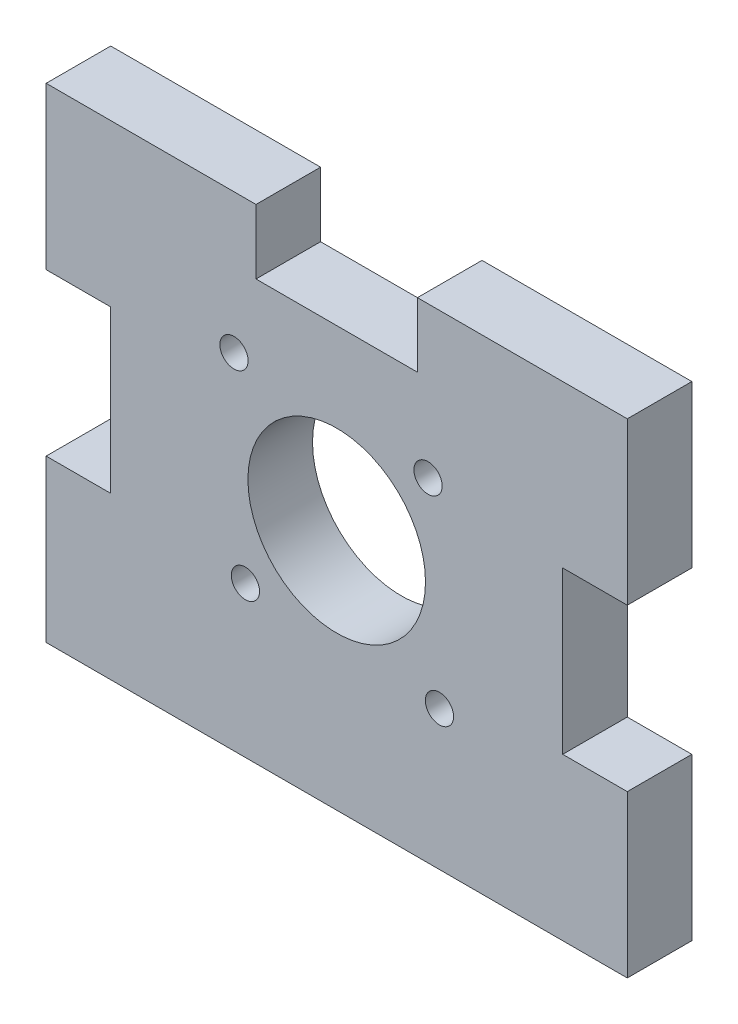
SolidWorks part; units mm, degrees
ref_plane "Front" through (0, 0, 0) normal (0, 0, 1) x (1, 0, 0)
ref_plane "Top" through (0, 0, 0) normal (0, 1, 0) x (1, 0, 0)
ref_plane "Right" through (0, 0, 0) normal (1, 0, 0) x (0, 0, -1)
sketch "Skizze1" plane through (0, 0, 0) normal (0, 0, 1) x (1, 0, 0)
  line L1 (18, 15) -> (-18, 15)
  line L2 (18, 15) -> (18, -15)
  line L3 (18, -15) -> (-18, -15)
  line L4 (-18, 15) -> (-18, -15)
  line L5 (18, 15) -> (-18, -15) construction
  line L6 (18, -15) -> (-18, 15) construction
  point P0 (0, 0)
  dimension "D1" = 36
  dimension "D2" = 30
extrude "Aufsatz-Linear austragen1" add sketch "Skizze1" along normal blind 4
sketch "Skizze2" plane through (0, 0, 4) normal (0, 0, 1) x (1, 0, 0)
  line L0 (0, 0) -> (0, 10.7157) construction
  line L1 (-5.6569, -5.6569) -> (5.6569, 5.6569) construction
  line L2 (-6.364, 6.364) -> (6.364, -6.364) construction
  circle A0 centre (0, 0) radius 5.5
  circle A1 centre (5.6569, 5.6569) radius 0.875
  circle A2 centre (6.364, -6.364) radius 0.875
  circle A3 centre (-5.6569, -5.6569) radius 0.875
  circle A4 centre (-6.364, 6.364) radius 0.875
  dimension "D1" = 11
  dimension "D3" = 1.75
  dimension "D2" = 45
  dimension "D4" = 16
  dimension "D5" = 18
extrude "Schnitt-Linear austragen1" cut sketch "Skizze2" against normal blind 4
sketch "Skizze3" plane through (0, 0, 4) normal (0, 0, 1) x (1, 0, 0)
  line L0 (18, 15) -> (-18, 15) construction
  line L2 (0, 0) -> (-18, 0) construction
  line L3 (-18, 15) -> (-18, -15) construction
  line L4 (-18, -5) -> (-18, 5)
  line L5 (-18, 5) -> (-14, 5)
  line L6 (-14, 5) -> (-14, -5)
  line L7 (-18, -5) -> (-14, -5)
  line L17 (-5, 15) -> (5, 15)
  line L18 (-5, 15) -> (-5, 11)
  line L19 (-5, 11) -> (5, 11)
  line L20 (5, 15) -> (5, 11)
  line L21 (0, 0) -> (0, 11) construction
  line L22 (18, -5) -> (14, -5)
  line L23 (14, 5) -> (14, -5)
  line L24 (18, 5) -> (14, 5)
  line L25 (18, -5) -> (18, 5)
  point P12 (-14, 0)
  point P21 (14, 0)
  dimension "D1" = 4
  dimension "D2" = 10
extrude "Schnitt-Linear austragen2" cut sketch "Skizze3" against normal through all
